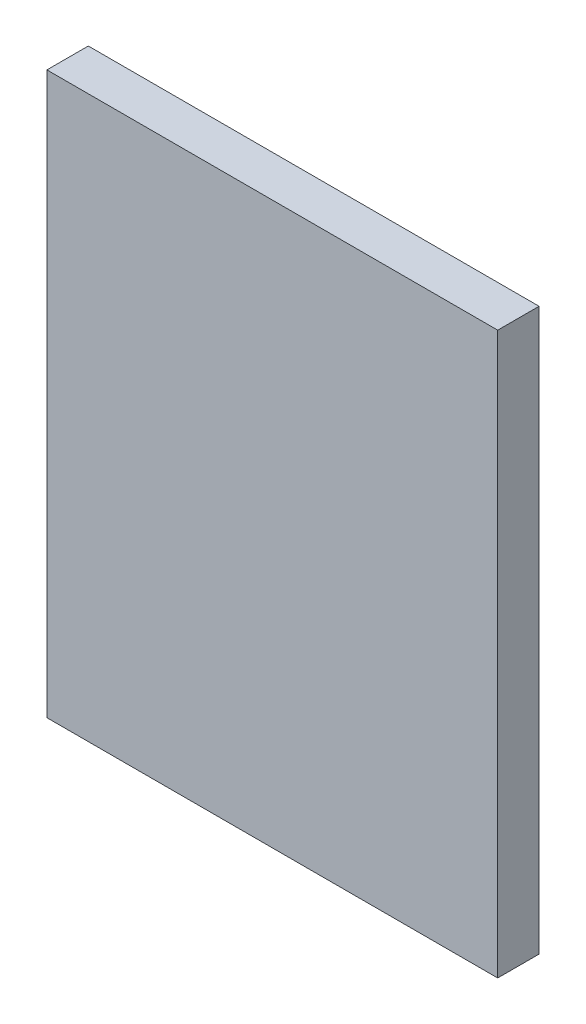
SolidWorks part; units mm, degrees
ref_plane "Ebene vorne" through (0, 0, 0) normal (0, 0, 1) x (1, 0, 0)
ref_plane "Ebene oben" through (0, 0, 0) normal (0, 1, 0) x (1, 0, 0)
ref_plane "Ebene rechts" through (0, 0, 0) normal (1, 0, 0) x (0, 0, -1)
sketch "Skizze1" plane through (0, 0, 0) normal (0, 0, 1) x (1, 0, 0)
  line L1 (-20.4077, 13.2205) -> (-2.9757, 13.2205)
  line L2 (-20.4077, 13.2205) -> (-20.4077, -8.4755)
  line L3 (-20.4077, -8.4755) -> (-2.9757, -8.4755)
  line L4 (-2.9757, 13.2205) -> (-2.9757, -8.4755)
  dimension "D1" = 17.432
  dimension "D2" = 21.696
extrude "Aufsatz-Linear austragen1" add sketch "Skizze1" along normal blind 1.6
